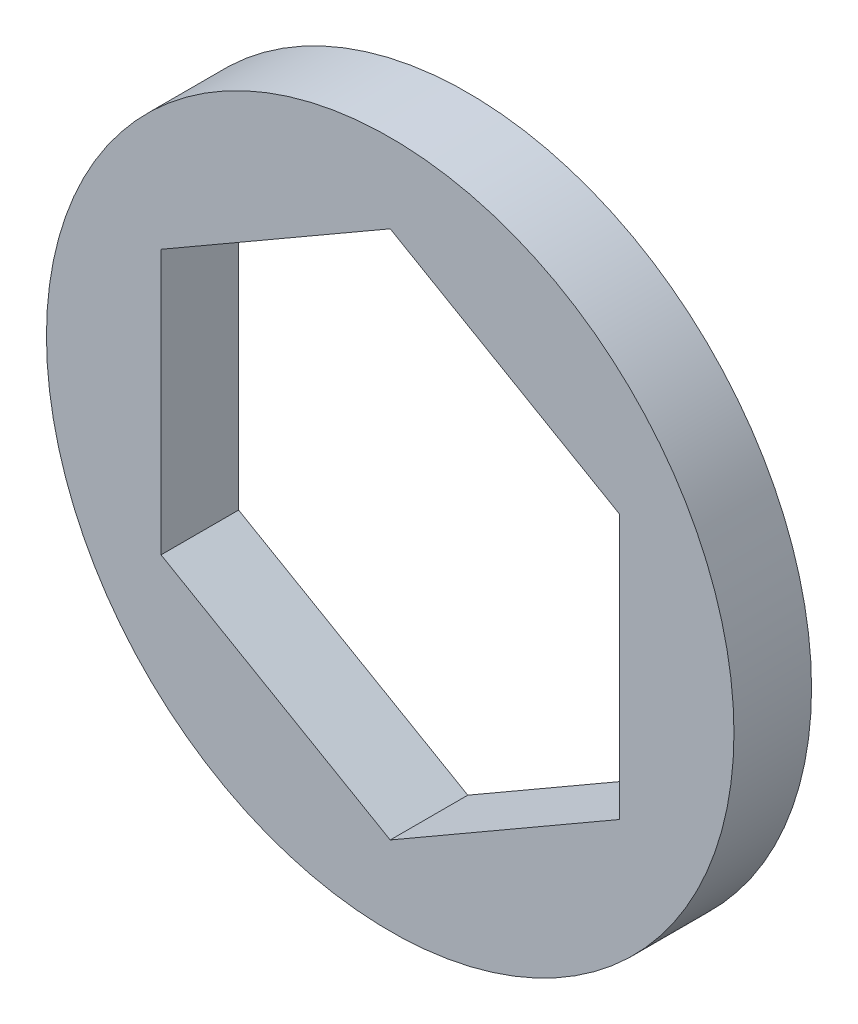
SolidWorks part; units mm, degrees
material "Nylon 101"
ref_plane "Front Plane" through (0, 0, 0) normal (0, 0, 1) x (1, 0, 0)
ref_plane "Top Plane" through (0, 0, 0) normal (0, 1, 0) x (1, 0, 0)
ref_plane "Right Plane" through (0, 0, 0) normal (1, 0, 0) x (0, 0, -1)
sketch "Sketch1" plane through (0, 0, 0) normal (0, 0, 1) x (1, 0, 0)
  line L1 (0, 7.3323) -> (-6.35, 3.6662)
  line L2 (-6.35, 3.6662) -> (-6.35, -3.6662)
  line L3 (-6.35, -3.6662) -> (0, -7.3323)
  line L4 (0, -7.3323) -> (6.35, -3.6662)
  line L5 (6.35, -3.6662) -> (6.35, 3.6662)
  line L6 (6.35, 3.6662) -> (0, 7.3323)
  circle A0 centre (0, 0) radius 9.525
  circle A1 centre (0, 0) radius 6.35 construction
  dimension "D1" = 12.7
  dimension "D2" = 19.05
extrude "Boss-Extrude1" add sketch "Sketch1" along normal mid plane 2.1496
